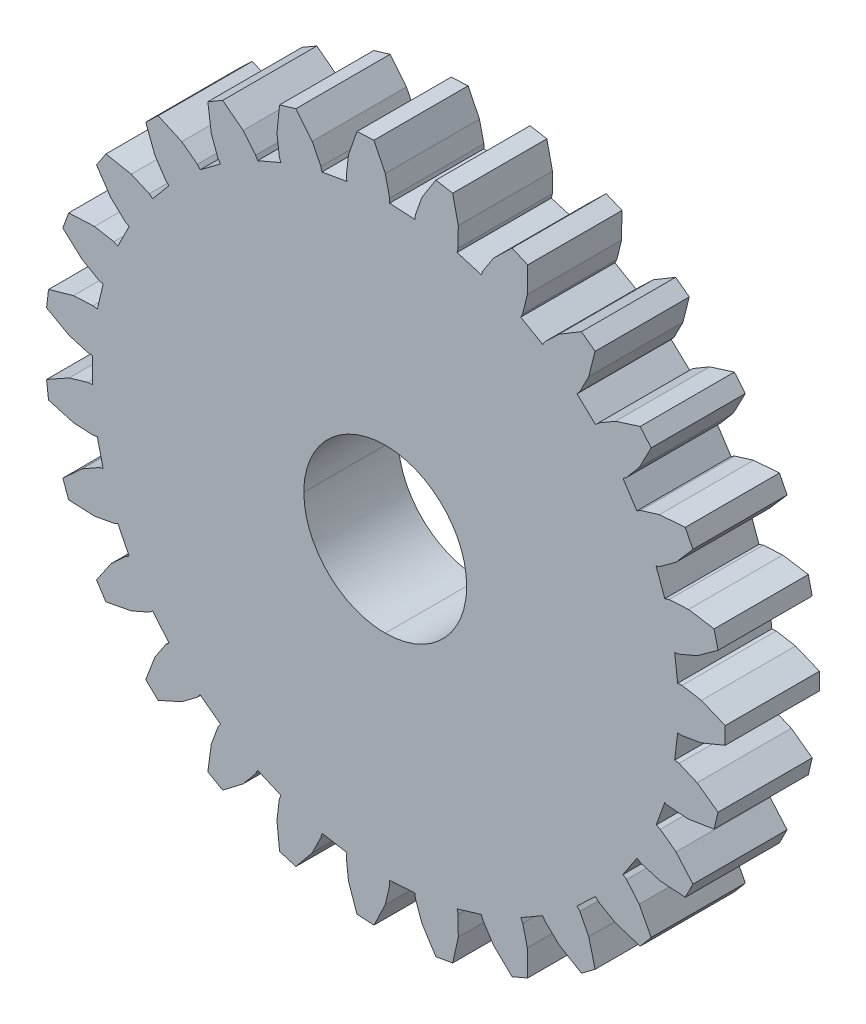
SolidWorks part; units mm, degrees
ref_plane "Front Plane" through (0, 0, 0) normal (0, 0, 1) x (1, 0, 0)
ref_plane "Top Plane" through (0, 0, 0) normal (0, 1, 0) x (1, 0, 0)
ref_plane "Right Plane" through (0, 0, 0) normal (1, 0, 0) x (0, 0, -1)
sketch "planet" plane through (-36.2254, 9.013, 0) normal (0, 0, 1) x (1, 0, 0)
  line L0 (108.2292, 209.5579) -> (108.3757, 209.5686)
  line L1 (108.3757, 209.5686) -> (109.0279, 209.4568)
  line L2 (109.0279, 209.4568) -> (109.8331, 209.1238)
  line L3 (109.8331, 209.1238) -> (109.8331, 208.5486)
  line L4 (109.8331, 208.5486) -> (109.0279, 208.2156)
  line L5 (109.0279, 208.2156) -> (108.3757, 208.1039)
  line L6 (108.3757, 208.1039) -> (108.2292, 208.1146)
  line L7 (108.2292, 208.1146) -> (108.1299, 207.2654)
  line L8 (108.1299, 207.2654) -> (108.275, 207.2422)
  line L9 (108.275, 207.2422) -> (108.884, 206.9829)
  line L10 (108.884, 206.9829) -> (109.5904, 206.4735)
  line L11 (109.5904, 206.4735) -> (109.4578, 205.9138)
  line L12 (109.4578, 205.9138) -> (108.5978, 205.7752)
  line L13 (108.5978, 205.7752) -> (107.9371, 205.817)
  line L14 (107.9371, 205.817) -> (107.7972, 205.8613)
  line L15 (107.7972, 205.8613) -> (107.5048, 205.0578)
  line L16 (107.5048, 205.0578) -> (107.6405, 205.0017)
  line L17 (107.6405, 205.0017) -> (108.1734, 204.6091)
  line L18 (108.1734, 204.6091) -> (108.7432, 203.9504)
  line L19 (108.7432, 203.9504) -> (108.4849, 203.4365)
  line L20 (108.4849, 203.4365) -> (107.6163, 203.5)
  line L21 (107.6163, 203.5) -> (106.9832, 203.693)
  line L22 (106.9832, 203.693) -> (106.8571, 203.7684)
  line L23 (106.8571, 203.7684) -> (106.3872, 203.0541)
  line L24 (106.3872, 203.0541) -> (106.5063, 202.968)
  line L25 (106.5063, 202.968) -> (106.9341, 202.4631)
  line L26 (106.9341, 202.4631) -> (107.3369, 201.6906)
  line L27 (107.3369, 201.6906) -> (106.9671, 201.2501)
  line L28 (106.9671, 201.2501) -> (106.1366, 201.5126)
  line L29 (106.1366, 201.5126) -> (105.5651, 201.8462)
  line L30 (105.5651, 201.8462) -> (105.4595, 201.9486)
  line L31 (105.4595, 201.9486) -> (104.8378, 201.3619)
  line L32 (104.8378, 201.3619) -> (104.9337, 201.2507)
  line L33 (104.9337, 201.2507) -> (105.2337, 200.6608)
  line L34 (105.2337, 200.6608) -> (105.4474, 199.8161)
  line L35 (105.4474, 199.8161) -> (104.9862, 199.4729)
  line L36 (104.9862, 199.4729) -> (104.2383, 199.9197)
  line L37 (104.2383, 199.9197) -> (103.7591, 200.3761)
  line L38 (103.7591, 200.3761) -> (103.6801, 200.5002)
  line L39 (103.6801, 200.5002) -> (102.9398, 200.0727)
  line L40 (102.9398, 200.0727) -> (103.0076, 199.9423)
  line L41 (103.0076, 199.9423) -> (103.1634, 199.2991)
  line L42 (103.1634, 199.2991) -> (103.1766, 198.4282)
  line L43 (103.1766, 198.4282) -> (102.6486, 198.2004)
  line L44 (102.6486, 198.2004) -> (102.024, 198.8075)
  line L45 (102.024, 198.8075) -> (101.6631, 199.3623)
  line L46 (101.6631, 199.3623) -> (101.6148, 199.5012)
  line L47 (101.6148, 199.5012) -> (100.7958, 199.2559)
  line L48 (100.7958, 199.2559) -> (100.8316, 199.1134)
  line L49 (100.8316, 199.1134) -> (100.835, 198.4516)
  line L50 (100.835, 198.4516) -> (100.6468, 197.601)
  line L51 (100.6468, 197.601) -> (100.0804, 197.5011)
  line L52 (100.0804, 197.5011) -> (99.6127, 198.236)
  line L53 (99.6127, 198.236) -> (99.3895, 198.8591)
  line L54 (99.3895, 198.8591) -> (99.3745, 199.0053)
  line L55 (99.3745, 199.0053) -> (98.5211, 198.9556)
  line L56 (98.5211, 198.9556) -> (98.5233, 198.8086)
  line L57 (98.5233, 198.8086) -> (98.3738, 198.164)
  line L58 (98.3738, 198.164) -> (97.9945, 197.3797)
  line L59 (97.9945, 197.3797) -> (97.4204, 197.413)
  line L60 (97.4204, 197.413) -> (97.1348, 198.236)
  line L61 (97.1348, 198.236) -> (97.0611, 198.8938)
  line L62 (97.0611, 198.8938) -> (97.0803, 199.0395)
  line L63 (97.0803, 199.0395) -> (96.2385, 199.1879)
  line L64 (96.2385, 199.1879) -> (96.2066, 199.0445)
  line L65 (96.2066, 199.0445) -> (95.9125, 198.4516)
  line L66 (95.9125, 198.4516) -> (95.3627, 197.7759)
  line L67 (95.3627, 197.7759) -> (94.8118, 197.9408)
  line L68 (94.8118, 197.9408) -> (94.7235, 198.8075)
  line L69 (94.7235, 198.8075) -> (94.8037, 199.4645)
  line L70 (94.8037, 199.4645) -> (94.8559, 199.6019)
  line L71 (94.8559, 199.6019) -> (94.071, 199.9406)
  line L72 (94.071, 199.9406) -> (94.0069, 199.8082)
  line L73 (94.0069, 199.8082) -> (93.5842, 199.2991)
  line L74 (93.5842, 199.2991) -> (92.8933, 198.7685)
  line L75 (92.8933, 198.7685) -> (92.3952, 199.0561)
  line L76 (92.3952, 199.0561) -> (92.5092, 199.9197)
  line L77 (92.5092, 199.9197) -> (92.7386, 200.5406)
  line L78 (92.7386, 200.5406) -> (92.8213, 200.6619)
  line L79 (92.8213, 200.6619) -> (92.1355, 201.1725)
  line L80 (92.1355, 201.1725) -> (92.0427, 201.0585)
  line L81 (92.0427, 201.0585) -> (91.5138, 200.6608)
  line L82 (91.5138, 200.6608) -> (90.7191, 200.3038)
  line L83 (90.7191, 200.3038) -> (90.3008, 200.6984)
  line L84 (90.3008, 200.6984) -> (90.611, 201.5126)
  line L85 (90.611, 201.5126) -> (90.9773, 202.0637)
  line L86 (90.9773, 202.0637) -> (91.0857, 202.1628)
  line L87 (91.0857, 202.1628) -> (90.5362, 202.8178)
  line L88 (90.5362, 202.8178) -> (90.4196, 202.7284)
  line L89 (90.4196, 202.7284) -> (89.8134, 202.4631)
  line L90 (89.8134, 202.4631) -> (88.9577, 202.2991)
  line L91 (88.9577, 202.2991) -> (88.6416, 202.7795)
  line L92 (88.6416, 202.7795) -> (89.1313, 203.5)
  line L93 (89.1313, 203.5) -> (89.615, 203.9518)
  line L94 (89.615, 203.9518) -> (89.7431, 204.0235)
  line L95 (89.7431, 204.0235) -> (89.3596, 204.7875)
  line L96 (89.3596, 204.7875) -> (89.2255, 204.7274)
  line L97 (89.2255, 204.7274) -> (88.5742, 204.6091)
  line L98 (88.5742, 204.6091) -> (87.7041, 204.6466)
  line L99 (87.7041, 204.6466) -> (87.5074, 205.1871)
  line L100 (87.5074, 205.1871) -> (88.1497, 205.7752)
  line L101 (88.1497, 205.7752) -> (88.7246, 206.1035)
  line L102 (88.7246, 206.1035) -> (88.866, 206.1435)
  line L103 (88.866, 206.1435) -> (88.6687, 206.9755)
  line L104 (88.6687, 206.9755) -> (88.5245, 206.9479)
  line L105 (88.5245, 206.9479) -> (87.8635, 206.9829)
  line L106 (87.8635, 206.9829) -> (87.0253, 207.2202)
  line L107 (87.0253, 207.2202) -> (86.9587, 207.7914)
  line L108 (86.9587, 207.7914) -> (87.7196, 208.2156)
  line L109 (87.7196, 208.2156) -> (88.3546, 208.4025)
  line L110 (88.3546, 208.4025) -> (88.5013, 208.4087)
  line L111 (88.5013, 208.4087) -> (88.5013, 209.2638)
  line L112 (88.5013, 209.2638) -> (88.3546, 209.27)
  line L113 (88.3546, 209.27) -> (87.7196, 209.4568)
  line L114 (87.7196, 209.4568) -> (86.9587, 209.881)
  line L115 (86.9587, 209.881) -> (87.0253, 210.4522)
  line L116 (87.0253, 210.4522) -> (87.8635, 210.6896)
  line L117 (87.8635, 210.6896) -> (88.5245, 210.7246)
  line L118 (88.5245, 210.7246) -> (88.6687, 210.6969)
  line L119 (88.6687, 210.6969) -> (88.866, 211.5289)
  line L120 (88.866, 211.5289) -> (88.7246, 211.569)
  line L121 (88.7246, 211.569) -> (88.1497, 211.8972)
  line L122 (88.1497, 211.8972) -> (87.5074, 212.4854)
  line L123 (87.5074, 212.4854) -> (87.7041, 213.0258)
  line L124 (87.7041, 213.0258) -> (88.5742, 213.0634)
  line L125 (88.5742, 213.0634) -> (89.2255, 212.9451)
  line L126 (89.2255, 212.9451) -> (89.3596, 212.885)
  line L127 (89.3596, 212.885) -> (89.7431, 213.649)
  line L128 (89.7431, 213.649) -> (89.615, 213.7207)
  line L129 (89.615, 213.7207) -> (89.1313, 214.1725)
  line L130 (89.1313, 214.1725) -> (88.6416, 214.893)
  line L131 (88.6416, 214.893) -> (88.9577, 215.3733)
  line L132 (88.9577, 215.3733) -> (89.8134, 215.2094)
  line L133 (89.8134, 215.2094) -> (90.4196, 214.9441)
  line L134 (90.4196, 214.9441) -> (90.5362, 214.8546)
  line L135 (90.5362, 214.8546) -> (91.0857, 215.5097)
  line L136 (91.0857, 215.5097) -> (90.9773, 215.6087)
  line L137 (90.9773, 215.6087) -> (90.611, 216.1599)
  line L138 (90.611, 216.1599) -> (90.3008, 216.9741)
  line L139 (90.3008, 216.9741) -> (90.7191, 217.3687)
  line L140 (90.7191, 217.3687) -> (91.5138, 217.0116)
  line L141 (91.5138, 217.0116) -> (92.0427, 216.614)
  line L142 (92.0427, 216.614) -> (92.1355, 216.5)
  line L143 (92.1355, 216.5) -> (92.8213, 217.0105)
  line L144 (92.8213, 217.0105) -> (92.7386, 217.1319)
  line L145 (92.7386, 217.1319) -> (92.5092, 217.7528)
  line L146 (92.5092, 217.7528) -> (92.3952, 218.6164)
  line L147 (92.3952, 218.6164) -> (92.8933, 218.9039)
  line L148 (92.8933, 218.9039) -> (93.5842, 218.3734)
  line L149 (93.5842, 218.3734) -> (94.0069, 217.8642)
  line L150 (94.0069, 217.8642) -> (94.071, 217.7319)
  line L151 (94.071, 217.7319) -> (94.8559, 218.0705)
  line L152 (94.8559, 218.0705) -> (94.8037, 218.208)
  line L153 (94.8037, 218.208) -> (94.7235, 218.865)
  line L154 (94.7235, 218.865) -> (94.8118, 219.7317)
  line L155 (94.8118, 219.7317) -> (95.3627, 219.8965)
  line L156 (95.3627, 219.8965) -> (95.9125, 219.2209)
  line L157 (95.9125, 219.2209) -> (96.2066, 218.6279)
  line L158 (96.2066, 218.6279) -> (96.2385, 218.4846)
  line L159 (96.2385, 218.4846) -> (97.0803, 218.633)
  line L160 (97.0803, 218.633) -> (97.0611, 218.7786)
  line L161 (97.0611, 218.7786) -> (97.1348, 219.4365)
  line L162 (97.1348, 219.4365) -> (97.4204, 220.2595)
  line L163 (97.4204, 220.2595) -> (97.9945, 220.2928)
  line L164 (97.9945, 220.2928) -> (98.3738, 219.5085)
  line L165 (98.3738, 219.5085) -> (98.5233, 218.8639)
  line L166 (98.5233, 218.8639) -> (98.5211, 218.7168)
  line L167 (98.5211, 218.7168) -> (99.3745, 218.6672)
  line L168 (99.3745, 218.6672) -> (99.3895, 218.8134)
  line L169 (99.3895, 218.8134) -> (99.6127, 219.4365)
  line L170 (99.6127, 219.4365) -> (100.0804, 220.1714)
  line L171 (100.0804, 220.1714) -> (100.6468, 220.0715)
  line L172 (100.6468, 220.0715) -> (100.835, 219.2209)
  line L173 (100.835, 219.2209) -> (100.8316, 218.5591)
  line L174 (100.8316, 218.5591) -> (100.7958, 218.4165)
  line L175 (100.7958, 218.4165) -> (101.6148, 218.1713)
  line L176 (101.6148, 218.1713) -> (101.6631, 218.3101)
  line L177 (101.6631, 218.3101) -> (102.024, 218.865)
  line L178 (102.024, 218.865) -> (102.6486, 219.4721)
  line L179 (102.6486, 219.4721) -> (103.1766, 219.2443)
  line L180 (103.1766, 219.2443) -> (103.1634, 218.3734)
  line L181 (103.1634, 218.3734) -> (103.0076, 217.7302)
  line L182 (103.0076, 217.7302) -> (102.9398, 217.5998)
  line L183 (102.9398, 217.5998) -> (103.6801, 217.1722)
  line L184 (103.6801, 217.1722) -> (103.7591, 217.2964)
  line L185 (103.7591, 217.2964) -> (104.2383, 217.7528)
  line L186 (104.2383, 217.7528) -> (104.9862, 218.1995)
  line L187 (104.9862, 218.1995) -> (105.4474, 217.8563)
  line L188 (105.4474, 217.8563) -> (105.2337, 217.0116)
  line L189 (105.2337, 217.0116) -> (104.9337, 216.4218)
  line L190 (104.9337, 216.4218) -> (104.8378, 216.3106)
  line L191 (104.8378, 216.3106) -> (105.4595, 215.7239)
  line L192 (105.4595, 215.7239) -> (105.5651, 215.8263)
  line L193 (105.5651, 215.8263) -> (106.1366, 216.1599)
  line L194 (106.1366, 216.1599) -> (106.9671, 216.4224)
  line L195 (106.9671, 216.4224) -> (107.3369, 215.9818)
  line L196 (107.3369, 215.9818) -> (106.9341, 215.2094)
  line L197 (106.9341, 215.2094) -> (106.5063, 214.7045)
  line L198 (106.5063, 214.7045) -> (106.3872, 214.6184)
  line L199 (106.3872, 214.6184) -> (106.8571, 213.9041)
  line L200 (106.8571, 213.9041) -> (106.9832, 213.9794)
  line L201 (106.9832, 213.9794) -> (107.6163, 214.1725)
  line L202 (107.6163, 214.1725) -> (108.4849, 214.236)
  line L203 (108.4849, 214.236) -> (108.7432, 213.7221)
  line L204 (108.7432, 213.7221) -> (108.1734, 213.0634)
  line L205 (108.1734, 213.0634) -> (107.6405, 212.6708)
  line L206 (107.6405, 212.6708) -> (107.5048, 212.6146)
  line L207 (107.5048, 212.6146) -> (107.7972, 211.8111)
  line L208 (107.7972, 211.8111) -> (107.9371, 211.8554)
  line L209 (107.9371, 211.8554) -> (108.5978, 211.8972)
  line L210 (108.5978, 211.8972) -> (109.4578, 211.7586)
  line L211 (109.4578, 211.7586) -> (109.5904, 211.199)
  line L212 (109.5904, 211.199) -> (108.884, 210.6896)
  line L213 (108.884, 210.6896) -> (108.275, 210.4302)
  line L214 (108.275, 210.4302) -> (108.1299, 210.4071)
  line L215 (108.1299, 210.4071) -> (108.2292, 209.5579)
  spline S0 degree 3 poles (101.1175, 208.8362) (101.1175, 207.3209) (99.8891, 206.0925) (98.3738, 206.0925) knots 0 0 0 0 1 1 1 1
  spline S1 degree 3 poles (98.3738, 206.0925) (96.8585, 206.0925) (95.6301, 207.3209) (95.6301, 208.8362) knots 0 0 0 0 1 1 1 1
  spline S2 degree 3 poles (95.6301, 208.8362) (95.6301, 210.3515) (96.8585, 211.5799) (98.3738, 211.5799) knots 0 0 0 0 1 1 1 1
  spline S3 degree 3 poles (98.3738, 211.5799) (99.8891, 211.5799) (101.1175, 210.3515) (101.1175, 208.8362) knots 0 0 0 0 1 1 1 1
extrude "Boss-Extrude3" add sketch "planet" along normal blind 3.175 separate body
